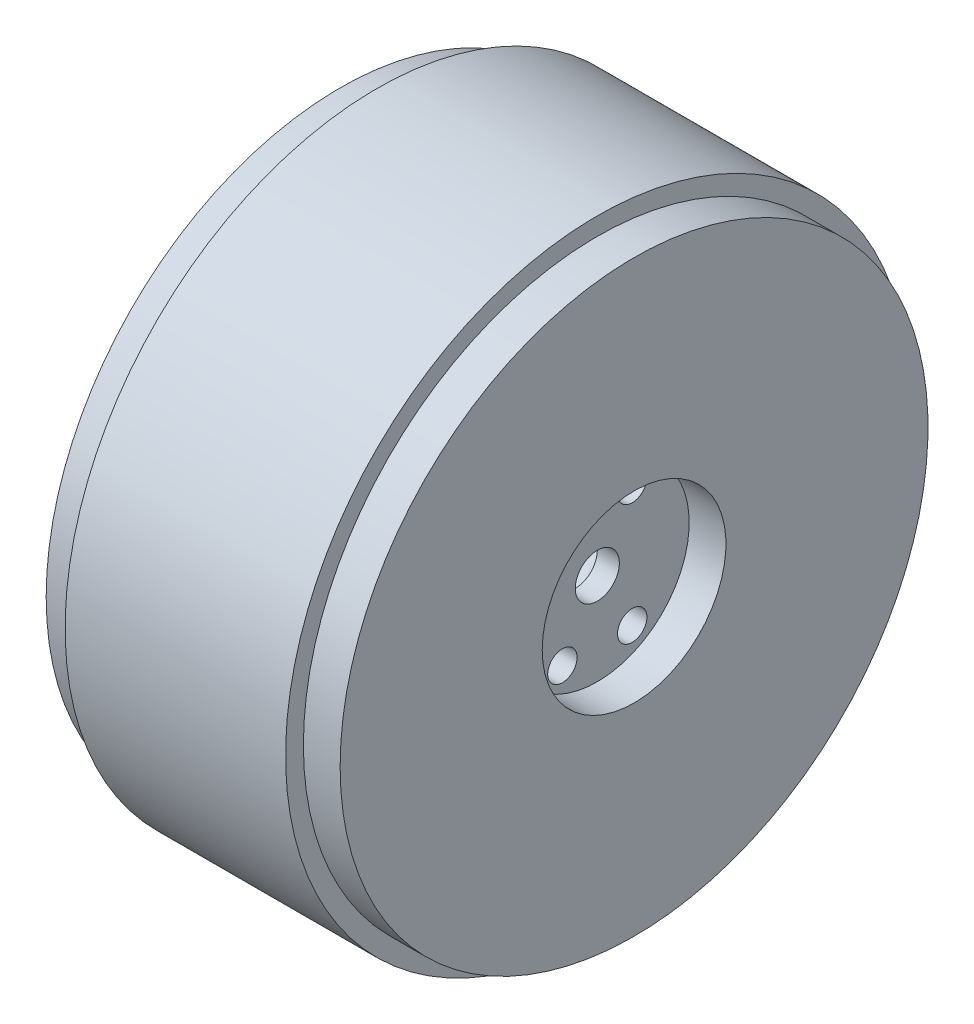
SolidWorks part; units mm, degrees
ref_plane "Plan de face" through (0, 0, 0) normal (0, 0, 1) x (1, 0, 0)
ref_plane "Plan de dessus" through (0, 0, 0) normal (0, 1, 0) x (1, 0, 0)
ref_plane "Plan de droite" through (0, 0, 0) normal (1, 0, 0) x (0, 0, -1)
sketch "Esquisse1" plane through (0, 0, 0) normal (0, 0, 1) x (1, 0, 0)
  line L0 (-49.6445, 0) -> (53.9199, 0) construction
  line L1 (0, 34) -> (0, 0)
  line L2 (0, 34) -> (-32, 34)
  line L3 (-32, 34) -> (-32, 40)
  line L4 (-32, 40) -> (-27, 40)
  line L5 (-27, 40) -> (-27, 39)
  line L6 (-27, 39) -> (3, 39)
  line L7 (3, 39) -> (3, 40)
  line L8 (3, 40) -> (8, 40)
  line L9 (8, 40) -> (8, 0)
  line L13 (0, 0) -> (8, 0)
  dimension "D2" = 5
  dimension "D3" = 5
  dimension "D4" = 40
  dimension "D5" = 1
  dimension "D6" = 8
  dimension "D10" = 6
  dimension "D11" = 1
  dimension "D12" = 30
revolve "Révolution1" add sketch "Esquisse1" angle 360 about L0
sketch "Esquisse2" plane through (0, 0, 0) normal (0, 0, 1) x (1, 0, 0)
  line L3 (0, 0) -> (8, 0) construction
  line L11 (8, -40) -> (8, 40) construction
  line L12 (8, 0) -> (8, 12.5)
  line L13 (8, 12.5) -> (3, 12.5)
  line L14 (3, 12.5) -> (3, 0)
  line L15 (3, 0) -> (8, 0)
  dimension "D1" = 25
  dimension "D2" = 5
revolve "Enlèvement de matière-Révolution1" cut sketch "Esquisse2" angle 360 about L3
sketch "Esquisse3" plane through (3, 0, 0) normal (1, 0, 0) x (0, 0, -1)
  line L0 (0, 12.5) -> (0, 0) construction
  line L1 (0, 0) -> (12.5, 0) construction
  line L2 (4.75, 8.2272) -> (0, 0) construction
  circle A0 centre (4.75, 8.2272) radius 2
  circle A2 centre (0, 0) radius 12.5 construction
  circle A3 centre (0, 0) radius 12.5 construction
  circle A4 centre (-4.75, 8.2272) radius 2
  circle A5 centre (4.75, -8.2272) radius 2
  circle A6 centre (-4.75, -8.2272) radius 2
  dimension "D1" = 4
  dimension "D2" = 9.5
  dimension "D3" = 30
extrude "Enlèv. mat.-Extru.1" cut sketch "Esquisse3" against normal through all
sketch "Esquisse4" plane through (3, 0, 0) normal (1, 0, 0) x (0, 0, -1)
  circle A0 centre (0, 0) radius 3
  dimension "D1" = 6
extrude "Enlèv. mat.-Extru.2" cut sketch "Esquisse4" against normal through all
sketch "Esquisse5" plane through (0, 0, 0) normal (0, 0, 1) x (1, 0, 0)
  line L0 (3, 39) -> (-27, 39) construction
  line L1 (3, 39) -> (-27, 39)
  line L2 (-27, 39) -> (-27, 42.4219)
  line L3 (-27, 42.4219) -> (3, 42.4219)
  line L4 (3, 42.4219) -> (3, 39)
  line L5 (0, 0) -> (-36.5095, 0) construction
  point P7 (3, 42.4219)
revolve "Révolution2" add sketch "Esquisse5" angle 360 about L5
